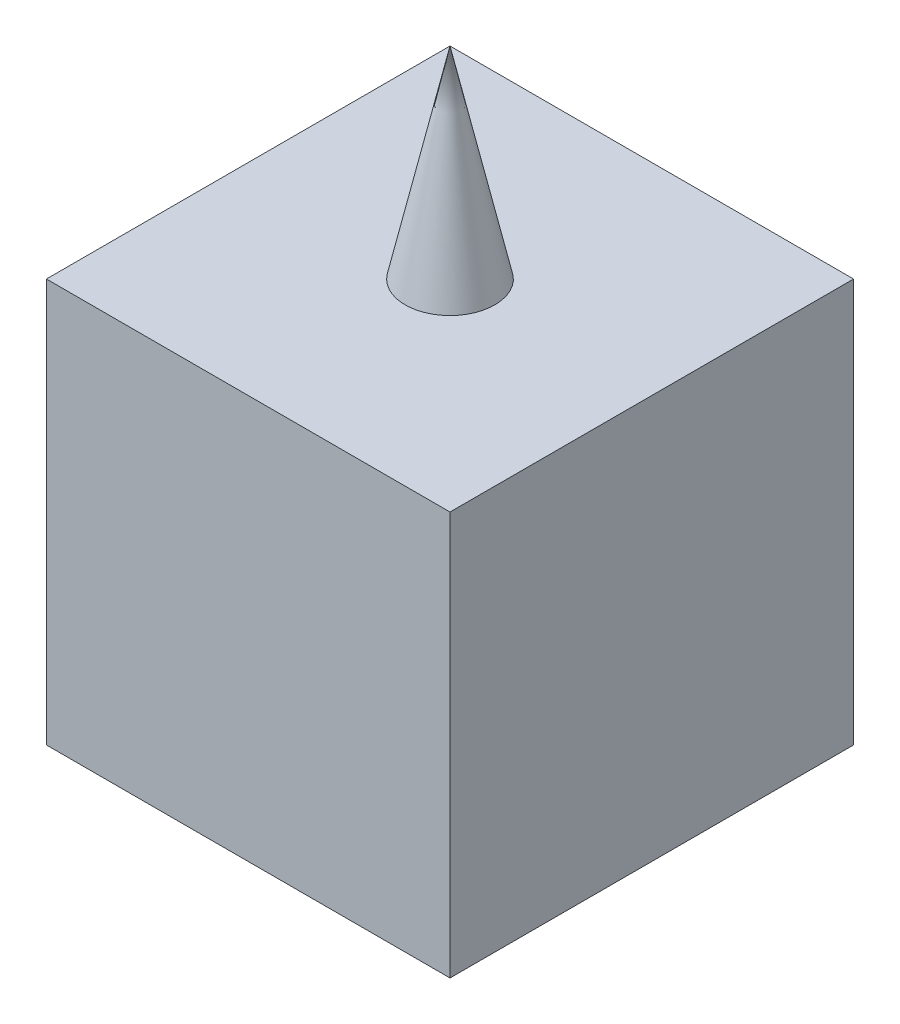
SolidWorks part; units mm, degrees
ref_plane "Front Plane" through (0, 0, 0) normal (0, 0, 1) x (1, 0, 0)
ref_plane "Top Plane" through (0, 0, 0) normal (0, 1, 0) x (1, 0, 0)
ref_plane "Right Plane" through (0, 0, 0) normal (1, 0, 0) x (0, 0, -1)
sketch "Sketch1" plane through (0, 0, 0) normal (0, 0, 1) x (1, 0, 0)
  line L1 (0, 0) -> (152.4, 0)
  line L2 (0, 0) -> (0, 152.4)
  line L3 (0, 152.4) -> (152.4, 152.4)
  line L4 (152.4, 0) -> (152.4, 152.4)
  dimension "D1" = 152.4
  dimension "D2" = 152.4
extrude "Cube" add sketch "Sketch1" along normal blind 152.4
sketch "Sketch2" plane through (0, 0, 0) normal (0, -1, 0) x (1, 0, 0)
  line L0 (0, 152.4) -> (152.4, 0) construction
  circle A0 centre (76.2, 76.2) radius 50.8
  dimension "D1" = 101.6
ref_plane "Plane1" through (0, 228.6, 0) normal (0, 1, 0) x (-1, 0, 0)
sketch "Sketch3" plane through (0, 228.6, 0) normal (0, 1, 0) x (-1, 0, 0)
  point P0 (-76.2, 76.2)
loft "Cone" add profiles "Sketch2", "Sketch3"
